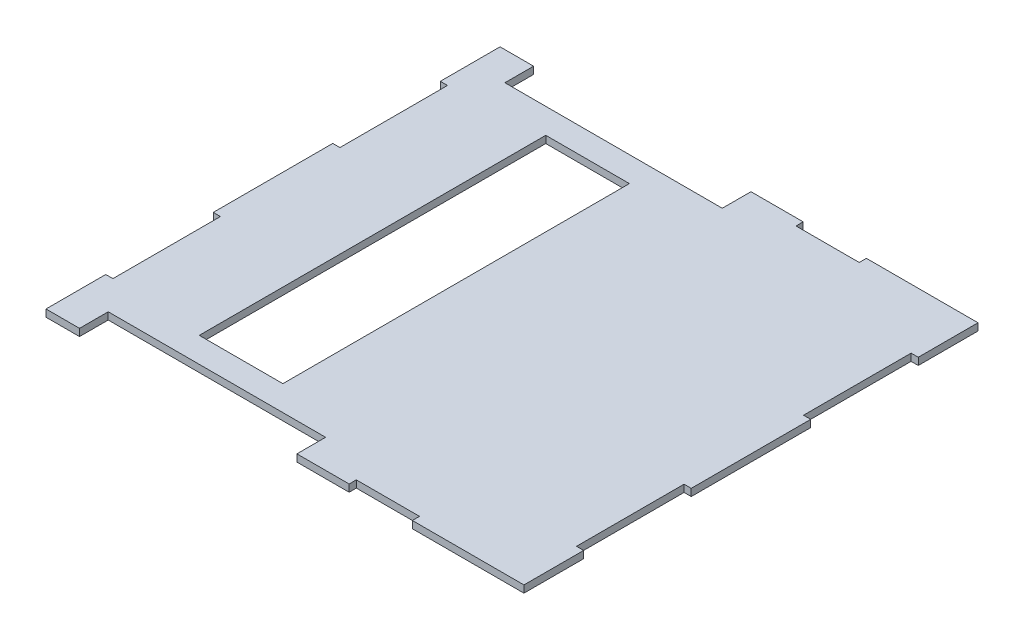
SolidWorks part; units mm, degrees
ref_plane "Front Plane" through (0, 0, 0) normal (0, 0, 1) x (1, 0, 0)
ref_plane "Top Plane" through (0, 0, 0) normal (0, 1, 0) x (1, 0, 0)
ref_plane "Right Plane" through (0, 0, 0) normal (1, 0, 0) x (0, 0, -1)
sketch "Sketch1" plane through (0, 0, 0) normal (0, 1, 0) x (1, 0, 0)
  line L1 (-100, -95) -> (100, -95)
  line L2 (-100, -95) -> (-100, 95)
  line L3 (-100, 95) -> (100, 95)
  line L4 (100, -95) -> (100, 95)
  line L5 (-100, -95) -> (100, 95) construction
  line L6 (-100, 95) -> (100, -95) construction
  point P0 (0, 0)
  dimension "D1" = 200
  dimension "D2" = 190
extrude "Boss-Extrude1" add sketch "Sketch1" along normal blind 3
sketch "Sketch2" plane through (0, 3, 0) normal (0, 1, 0) x (1, 0, 0)
  line L0 (-100, -95) -> (-100, -70)
  line L1 (-100, 95) -> (-100, -95) construction
  line L2 (-100, -70) -> (-97, -70)
  line L3 (-97, -70) -> (-97, -25)
  line L4 (-97, -25) -> (-100, -25)
  line L5 (-100, -25) -> (-100, 25)
  line L6 (-1000, 0) -> (49000, 0) construction
  line L7 (-97, 25) -> (-100, 25)
  line L8 (-97, 70) -> (-97, 25)
  line L9 (-100, 70) -> (-97, 70)
  line L10 (-100, 95) -> (-100, 70)
  line L11 (0, -1000) -> (0, 49000) construction
  line L12 (100, 95) -> (100, 70)
  line L13 (100, 70) -> (97, 70)
  line L14 (97, 70) -> (97, 25)
  line L15 (97, 25) -> (100, 25)
  line L16 (100, -25) -> (100, 25)
  line L17 (97, -25) -> (100, -25)
  line L18 (97, -70) -> (97, -25)
  line L19 (100, -70) -> (97, -70)
  line L20 (100, -95) -> (100, -70)
  line L21 (-100, -95) -> (100, -95)
  line L22 (-100, 95) -> (100, 95)
  point P13 (-100, 0)
  point P29 (100, 0)
  dimension "D1" = 25
  dimension "D2" = 25
  dimension "D3" = 3
extrude "Cut-Extrude2" cut sketch "Sketch2" against normal blind 3 and the other way through all flip side to cut
sketch "Sketch3" plane through (0, 3, 0) normal (0, 1, 0) x (1, 0, 0)
  line L1 (-58.3736, -72.5) -> (-23.3736, -72.5)
  line L2 (-58.3736, -72.5) -> (-58.3736, 72.5)
  line L3 (-58.3736, 72.5) -> (-23.3736, 72.5)
  line L4 (-23.3736, -72.5) -> (-23.3736, 72.5)
  line L5 (-58.3736, -72.5) -> (-23.3736, 72.5) construction
  line L6 (-58.3736, 72.5) -> (-23.3736, -72.5) construction
  point P0 (-40.8736, 0)
  point P5 (-58.3736, 0)
  dimension "D1" = 145
  dimension "D2" = 0
  dimension "D3" = 35
extrude "Cut-Extrude3" cut sketch "Sketch3" against normal blind 3
sketch "Sketch4" plane through (0, 3, 0) normal (0, 1, 0) x (1, 0, 0)
  line L0 (100, 95) -> (-100, 95) construction
  line L1 (-85.9687, 83) -> (5, 83)
  line L2 (-85.9687, 83) -> (-85.9687, 95)
  line L3 (-85.9687, 95) -> (5, 95)
  line L4 (5, 83) -> (5, 95)
  line L5 (-85.9687, 83) -> (5, 95) construction
  line L6 (-85.9687, 95) -> (5, 83) construction
  line L8 (-1000, 0) -> (49000, 0) construction
  line L9 (-85.9687, -95) -> (5, -83) construction
  line L10 (-85.9687, -83) -> (5, -95) construction
  line L11 (5, -83) -> (5, -95)
  line L12 (-85.9687, -95) -> (5, -95)
  line L13 (-85.9687, -83) -> (-85.9687, -95)
  line L14 (-85.9687, -83) -> (5, -83)
  line L15 (100, 70) -> (100, 95) construction
  point P0 (-40.4843, 89)
  point P7 (-64.5063, 89)
  point P8 (-65.7145, 89)
  point P17 (-40.4843, -89)
  dimension "D2" = 12
  dimension "D3" = 95
extrude "Cut-Extrude4" cut sketch "Sketch4" against normal blind 3
sketch "Sketch6" plane through (0, 0, 95) normal (0, 0, 1) x (1, 0, 0)
  line L0 (26.8518, 0) -> (26.8518, 3)
  line L1 (5, 0) -> (100, 0) construction
  line L2 (5, 3) -> (100, 3) construction
  line L3 (26.8518, 3) -> (53.3081, 3)
  line L4 (53.3081, 3) -> (53.3081, 0)
  line L5 (53.3081, 0) -> (26.8518, 0)
  line L6 (28.7118, -23.3998) -> (27.7888, -20.6149)
  line L7 (27.7888, -20.6149) -> (57.8344, -10.6569)
  line L8 (57.8344, -10.6569) -> (58.8057, -13.5874)
  line L9 (58.8057, -13.5874) -> (28.7118, -23.3998)
extrude "Cut-Extrude5" cut sketch "Sketch6" against normal blind 3
mirror "Mirror1" about plane through (0, 0, 0) normal (0, 0, 1) of "Cut-Extrude5"
